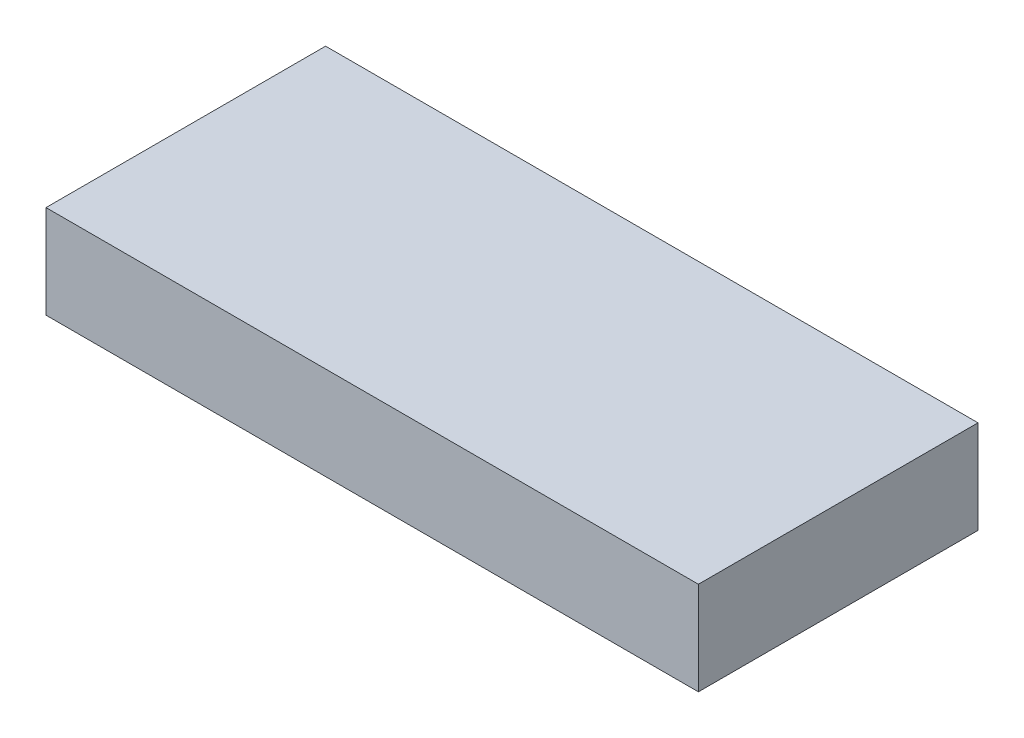
SolidWorks part; units mm, degrees
ref_plane "Front Plane" through (0, 0, 0) normal (0, 0, 1) x (1, 0, 0)
ref_plane "Top Plane" through (0, 0, 0) normal (0, 1, 0) x (1, 0, 0)
ref_plane "Right Plane" through (0, 0, 0) normal (1, 0, 0) x (0, 0, -1)
sketch "Sketch1" plane through (0, 0, 0) normal (0, 1, 0) x (1, 0, 0)
  line L1 (-35, -15) -> (35, -15)
  line L2 (-35, -15) -> (-35, 15)
  line L3 (-35, 15) -> (35, 15)
  line L4 (35, -15) -> (35, 15)
  line L5 (-35, -15) -> (35, 15) construction
  line L6 (-35, 15) -> (35, -15) construction
  point P0 (0, 0)
  dimension "D1" = 70
  dimension "D2" = 30
extrude "Boss-Extrude1" add sketch "Sketch1" along normal blind 10
